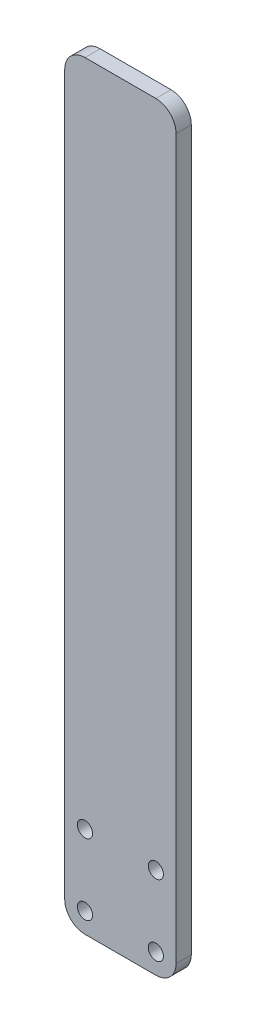
SolidWorks part; units mm, degrees
ref_plane "Plan de face" through (0, 0, 0) normal (0, 0, 1) x (1, 0, 0)
ref_plane "Plan de dessus" through (0, 0, 0) normal (0, 1, 0) x (1, 0, 0)
ref_plane "Plan de droite" through (0, 0, 0) normal (1, 0, 0) x (0, 0, -1)
sketch "Esquisse1" plane through (0, 0, 0) normal (0, 0, 1) x (1, 0, 0)
  line L0 (0, 150) -> (0, 0) construction
  line L1 (-11, 150) -> (11, 150)
  line L2 (-11, 150) -> (-11, 0)
  line L3 (-11, 0) -> (11, 0)
  line L4 (11, 150) -> (11, 0)
  line L6 (-11, 11) -> (11, 11) construction
  circle A0 centre (7, 4) radius 1.5
  circle A1 centre (-7, 4) radius 1.5
  circle A2 centre (7, 18) radius 1.5
  circle A3 centre (-7, 18) radius 1.5
  dimension "D4" = 3
  dimension "D1" = 22
  dimension "D2" = 11
  dimension "D5" = 4
  dimension "D6" = 4
  dimension "D7" = 150
extrude "Boss.-Extru.1" add sketch "Esquisse1" along normal blind 3
fillet "Congé1" radius 4 4 edges at (11, 150, 1.5) (-11, 150, 1.5) (-11, 0, 1.5) (11, 0, 1.5)
